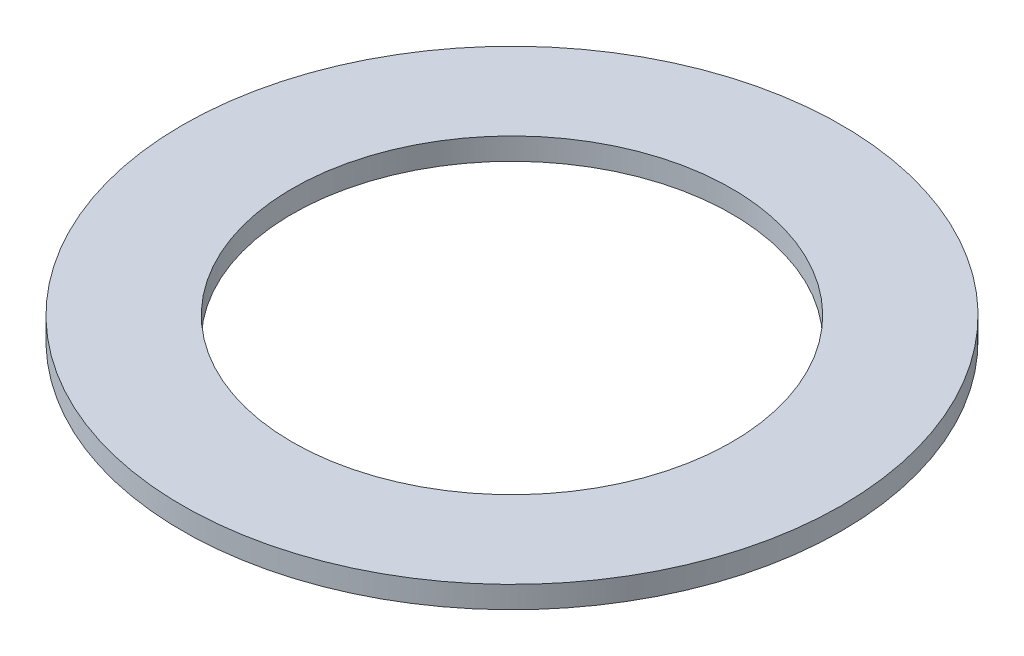
SolidWorks part; units mm, degrees
material "Plain Carbon Steel"
ref_plane "Front Plane" through (0, 0, 0) normal (0, 0, 1) x (1, 0, 0)
ref_plane "Top Plane" through (0, 0, 0) normal (0, 1, 0) x (1, 0, 0)
ref_plane "Right Plane" through (0, 0, 0) normal (1, 0, 0) x (0, 0, -1)
sketch "Sketch1" plane through (0, 0, 0) normal (0, 1, 0) x (1, 0, 0)
  circle A0 centre (0, 0) radius 10
  dimension "D1" = 20
extrude "Extrude-Thin1" add sketch "Sketch1" along normal blind 1 thin
